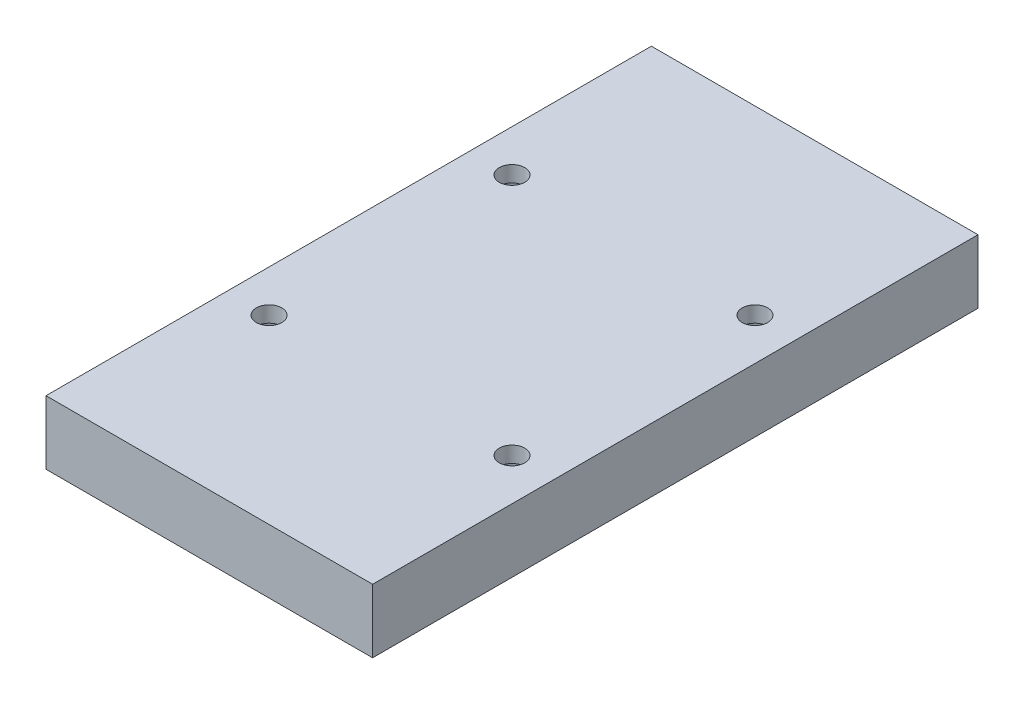
SolidWorks part; units mm, degrees
ref_plane "Front Plane" through (0, 0, 0) normal (0, 0, 1) x (1, 0, 0)
ref_plane "Top Plane" through (0, 0, 0) normal (0, 1, 0) x (1, 0, 0)
ref_plane "Right Plane" through (0, 0, 0) normal (1, 0, 0) x (0, 0, -1)
sketch "Sketch1" plane through (0, 0, 0) normal (0, 1, 0) x (1, 0, 0)
  line L1 (17.5, 35) -> (-17.5, 35)
  line L2 (17.5, 35) -> (17.5, -35)
  line L3 (17.5, -35) -> (-17.5, -35)
  line L4 (-17.5, 35) -> (-17.5, -35)
  line L5 (17.5, 35) -> (-17.5, -35) construction
  line L6 (17.5, -35) -> (-17.5, 35) construction
  point P0 (0, 0)
  dimension "D1" = 35
  dimension "D2" = 70
extrude "Boss-Extrude1" add sketch "Sketch1" against normal blind 5
sketch "Sketch3" plane through (0, 0, 0) normal (0, 1, 0) x (1, 0, 0)
  line L1 (15.25, 15.25) -> (-15.25, 15.25)
  line L2 (15.25, 15.25) -> (15.25, -15.25)
  line L3 (15.25, -15.25) -> (-15.25, -15.25)
  line L4 (-15.25, 15.25) -> (-15.25, -15.25)
  line L5 (15.25, 15.25) -> (-15.25, -15.25) construction
  line L6 (15.25, -15.25) -> (-15.25, 15.25) construction
  point P0 (0, 0)
  dimension "D1" = 30.5
  dimension "D2" = 30.5
sketch "Sketch9" plane through (0, -5, 0) normal (0, 1, 0) x (1, 0, 0)
  line L4 (17.5, 35) -> (-17.5, 35)
  line L5 (-17.5, 35) -> (-17.5, -35)
  line L6 (-17.5, -35) -> (17.5, -35)
  line L7 (17.5, -35) -> (17.5, 35)
  line L8 (17.5, 35) -> (-17.5, 35)
  line L9 (-17.5, 35) -> (-17.5, -35)
  line L10 (-17.5, -35) -> (17.5, -35)
  line L11 (17.5, -35) -> (17.5, 35)
  dimension "D1" = 0
extrude "Extrude-Thin1" add sketch "Sketch9" against normal blind 3 and the other way blind 5 thin
hole_wizard "Ø3.2 (3.2) Diameter Hole1" positions "Sketch4" profile "Sketch5" hole size "Ø3.2" standard "ISO" end condition through all
sketch "Sketch4" plane through (0, -5, 0) normal (0, -1, 0) x (-1, 0, 0)
  point P0 (15.25, 15.25)
  point P3 (15.25, -15.25)
  point P6 (-15.25, -15.25)
  point P9 (-15.25, 15.25)
sketch "Sketch5" plane through (-15.25, -5, -15.25) normal (1, 0, 0) x (0, 0, -1)
  line L0 (0, 0) -> (0, 5)
  line L1 (0, 5) -> (1.6, 5)
  line L2 (1.6, 5) -> (1.6, 0)
  line L5 (1.6, 0) -> (0, 0)
  line L11 (0, -6.35) -> (0, 107.95) construction
  dimension "Thru Hole Dia." = 3.2
  dimension "Thru Hole Depth" = 5
sketch "Sketch8" plane through (0, -5, 0) normal (0, -1, 0) x (1, 0, 0)
  circle A0 centre (-15.25, 15.25) radius 3
  circle A1 centre (15.25, 15.25) radius 3
  circle A2 centre (15.25, -15.25) radius 3
  circle A3 centre (-15.25, -15.25) radius 3
  dimension "D1" = 6
extrude "Cut-Extrude1" cut sketch "Sketch8" against normal blind 3 and the other way through all
